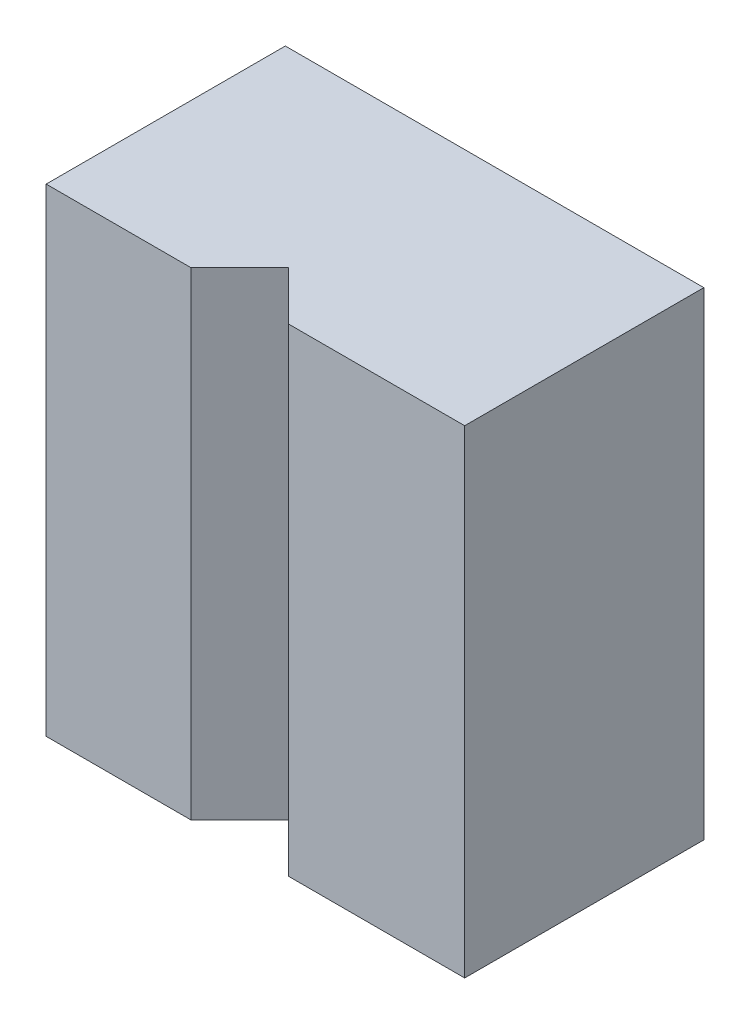
SolidWorks part; units mm, degrees
material "Pine"
ref_plane "X-Y Datum" through (0, 0, 0) normal (0, 0, 1) x (1, 0, 0)
ref_plane "X-Z Datum" through (0, 0, 0) normal (0, 1, 0) x (1, 0, 0)
ref_plane "Y-Z Datum" through (0, 0, 0) normal (1, 0, 0) x (0, 0, -1)
sketch "Sketch1" plane through (0, 0, 0) normal (0, 1, 0) x (1, 0, 0)
  line L1 (0, 0) -> (-101.6, 0)
  line L2 (0, 0) -> (0, 50.8)
  line L3 (0, 50.8) -> (-101.6, 50.8)
  line L4 (-101.6, 0) -> (-101.6, 50.8)
  dimension "D1" = 101.6
  dimension "D2" = 50.8
extrude "Boss-Extrude1" add sketch "Sketch1" along normal blind 101.6
sketch "Sketch2" plane through (0, 101.6, 0) normal (0, 1, 0) x (1, 0, 0)
  line L0 (-37.465, 0) -> (-47.7923, 10.3273)
  line L1 (-101.6, 0) -> (0, 0) construction
  line L2 (-47.7923, 10.3273) -> (-58.1196, 0)
  dimension "D1" = 135
  dimension "D2" = 14.605
  dimension "D3" = 37.465
extrude "Cut-Extrude1" cut sketch "Sketch2" against normal through all both and the other way through all
sketch "Sketch3" plane through (0, 0, 0) normal (0, -1, 0) x (1, 0, 0)
  line L0 (0, -50.8) -> (-101.6, -50.8) construction
  line L1 (-101.6, 0) -> (-88.9, 0)
  line L2 (-101.6, 0) -> (-101.6, -50.8)
  line L3 (-101.6, -50.8) -> (-88.9, -50.8)
  line L4 (-88.9, 0) -> (-88.9, -50.8)
  dimension "D1" = 12.7
extrude "Cut-Extrude2" cut sketch "Sketch3" against normal through all both
